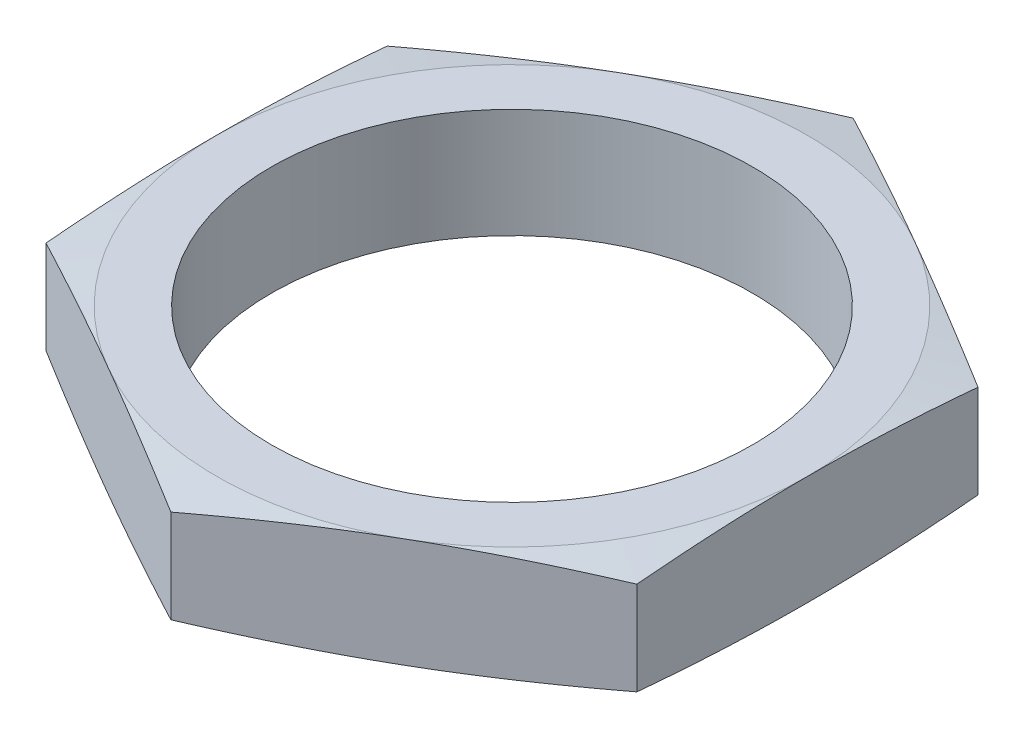
SolidWorks part; units mm, degrees
ref_plane "Alzado" through (0, 0, 0) normal (0, 0, 1) x (1, 0, 0)
ref_plane "Planta" through (0, 0, 0) normal (0, 1, 0) x (1, 0, 0)
ref_plane "Vista lateral" through (0, 0, 0) normal (1, 0, 0) x (0, 0, -1)
sketch "Croquis1" plane through (0, 0, 0) normal (0, 1, 0) x (1, 0, 0)
  line L1 (0, 15.5885) -> (-13.5, 7.7942)
  line L2 (-13.5, 7.7942) -> (-13.5, -7.7942)
  line L3 (-13.5, -7.7942) -> (0, -15.5885)
  line L4 (0, -15.5885) -> (13.5, -7.7942)
  line L5 (13.5, -7.7942) -> (13.5, 7.7942)
  line L6 (13.5, 7.7942) -> (0, 15.5885)
  circle A0 centre (0, 0) radius 11
  circle A1 centre (0, 0) radius 13.5 construction
  dimension "D1" = 22
extrude "Saliente-Extruir1" add sketch "Croquis1" along normal blind 5
sketch "Croquis2" plane through (0, 5, 0) normal (0, 1, 0) x (1, 0, 0)
  circle A0 centre (0, 0) radius 13.5
extrude "Cortar-Extruir1" cut sketch "Croquis2" against normal through all draft 80 flip side to cut
sketch "Croquis3" plane through (0, 0, 0) normal (0, -1, 0) x (1, 0, 0)
  circle A0 centre (0, 0) radius 13.5
extrude "Cortar-Extruir2" cut sketch "Croquis3" against normal blind 5 draft 80 flip side to cut
